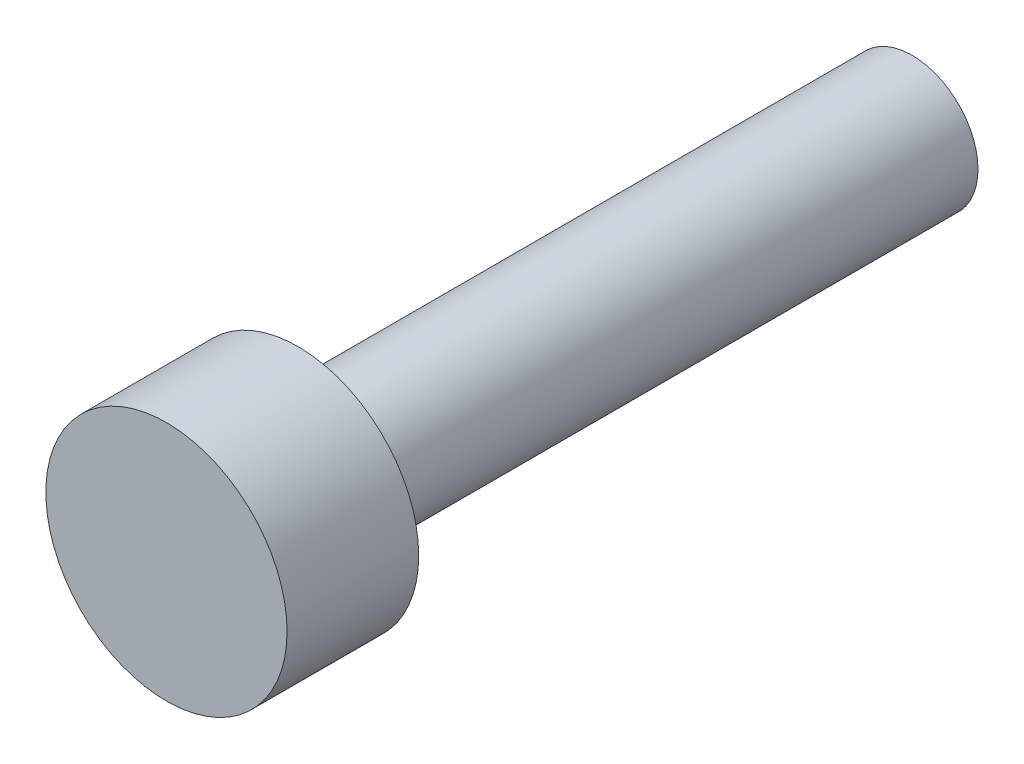
SolidWorks part; units mm, degrees
ref_plane "Front Plane" through (0, 0, 0) normal (0, 0, 1) x (1, 0, 0)
ref_plane "Top Plane" through (0, 0, 0) normal (0, 1, 0) x (1, 0, 0)
ref_plane "Right Plane" through (0, 0, 0) normal (1, 0, 0) x (0, 0, -1)
sketch "Shank_nominal_thread_envelope_profile" plane through (0, 0, 0) normal (0, 0, 1) x (1, 0, 0)
  circle A0 centre (0, 0) radius 1.5
  dimension "D1" = 3
extrude "Shank_nominal_thread_envelope" add sketch "Shank_nominal_thread_envelope_profile" along normal blind 14 from offset 14
sketch "Socket_head_envelope_profile" plane through (0, 0, 0) normal (0, 0, 1) x (1, 0, 0)
  circle A0 centre (0, 0) radius 2.75
  dimension "D1" = 5.5
extrude "Socket_head_envelope" add sketch "Socket_head_envelope_profile" along normal blind 3
